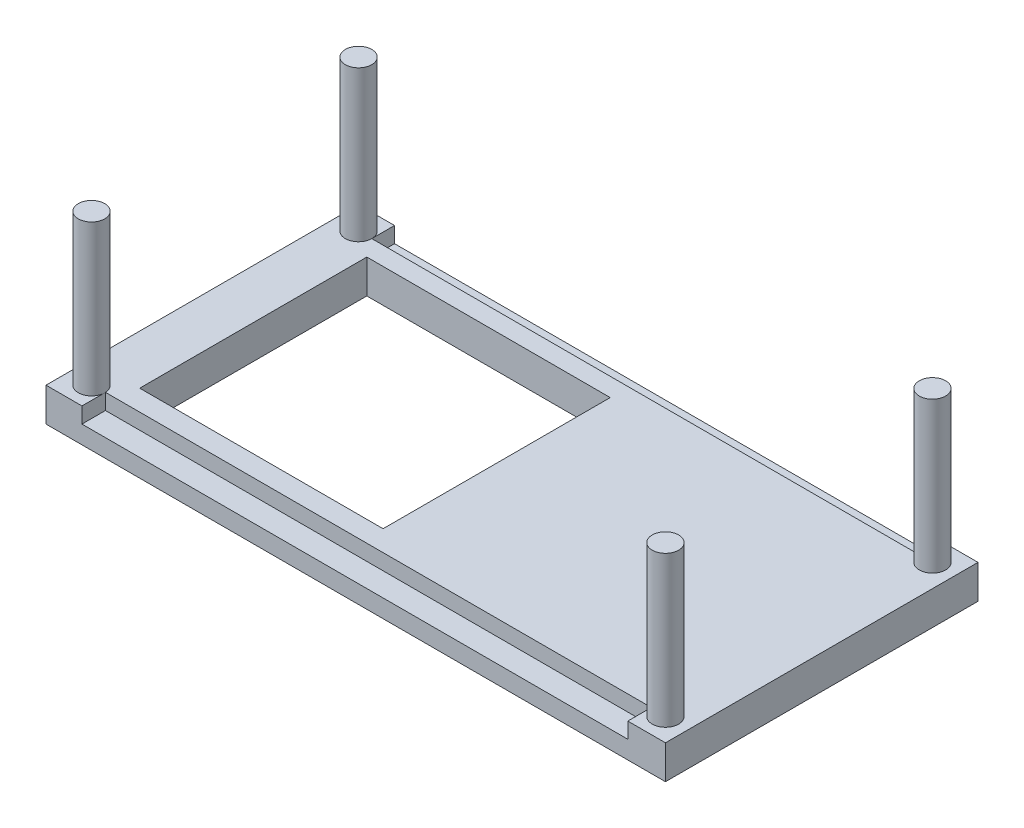
SolidWorks part; units mm, degrees
ref_plane "Front Plane" through (0, 0, 0) normal (0, 0, 1) x (1, 0, 0)
ref_plane "Top Plane" through (0, 0, 0) normal (0, 1, 0) x (1, 0, 0)
ref_plane "Right Plane" through (0, 0, 0) normal (1, 0, 0) x (0, 0, -1)
sketch "Sketch1" plane through (0, 0, 0) normal (0, 1, 0) x (1, 0, 0)
  line L1 (27.55, -13.9) -> (-27.55, -13.9)
  line L2 (27.55, -13.9) -> (27.55, 13.9)
  line L3 (27.55, 13.9) -> (-27.55, 13.9)
  line L4 (-27.55, -13.9) -> (-27.55, 13.9)
  line L5 (27.55, -13.9) -> (-27.55, 13.9) construction
  line L6 (27.55, 13.9) -> (-27.55, -13.9) construction
  point P0 (0, 0)
  dimension "D1" = 27.8
  dimension "D2" = 55.1
extrude "Boss-Extrude1" add sketch "Sketch1" along normal blind 3
sketch "Sketch2" plane through (0, 3, 0) normal (0, 1, 0) x (1, 0, 0)
  line L0 (26.7, -11.875) -> (27.55, -11.875)
  line L1 (25.525, -13.05) -> (25.525, -13.9)
  line L2 (-27.55, -13.9) -> (27.55, -13.9) construction
  line L3 (27.55, -13.9) -> (27.55, 13.9) construction
  line L4 (25.525, 13.05) -> (25.525, 13.9)
  line L5 (27.55, 13.9) -> (-27.55, 13.9) construction
  line L6 (26.7, 11.875) -> (27.55, 11.875)
  line L7 (-25.525, 13.05) -> (-25.525, 13.9)
  line L8 (-26.7, 11.875) -> (-27.55, 11.875)
  line L9 (-27.55, 13.9) -> (-27.55, -13.9) construction
  line L10 (-26.7, -11.875) -> (-27.55, -11.875)
  line L11 (-25.525, -13.05) -> (-25.525, -13.9)
  circle A0 centre (25.525, -11.875) radius 1.175
  circle A1 centre (25.525, 11.875) radius 1.175
  circle A2 centre (-25.525, 11.875) radius 1.175
  circle A3 centre (-25.525, -11.875) radius 1.175
  dimension "D1" = 2.35
  dimension "D2" = 0.85
  dimension "D4" = 2.35
  dimension "D7" = 2.35
  dimension "D10" = 2.35
  dimension "D3" = 0.85
  dimension "D5" = 0.85
  dimension "D6" = 0.85
  dimension "D8" = 0.85
  dimension "D9" = 0.85
  dimension "D11" = 0.85
  dimension "D12" = 0.85
extrude "Boss-Extrude2" add sketch "Sketch2" along normal blind 13.4 contours A2 | A3 | A1 | A0
sketch "Sketch3" plane through (0, 0, 0) normal (0, -1, 0) x (1, 0, 0)
  line L0 (-27.55, -13.9) -> (-27.55, 13.9) construction
  line L1 (-3.5, -8.25) -> (-21.15, -8.25)
  line L2 (-3.5, -8.25) -> (-3.5, 7.5)
  line L3 (-3.5, 7.5) -> (-21.15, 7.5)
  line L4 (-21.15, -8.25) -> (-21.15, 7.5)
  line L5 (-27.55, 13.9) -> (27.55, 13.9) construction
  line L6 (27.55, -13.9) -> (-27.55, -13.9) construction
  line L8 (-1.5, -10.2373) -> (-23.15, -10.2373)
  line L9 (-1.5, -10.2373) -> (-1.5, 9.9665)
  line L10 (-1.5, 9.9665) -> (-23.15, 9.9665)
  line L11 (-23.15, -10.2373) -> (-23.15, 9.9665)
  line L12 (-3.5, 7.5) -> (-21.15, 7.5)
  line L13 (-3.5, 7.5) -> (-3.5, -8.25)
  line L14 (-3.5, -8.25) -> (-21.15, -8.25)
  line L15 (-21.15, 7.5) -> (-21.15, -8.25)
  dimension "D1" = 15.75
  dimension "D2" = 17.65
  dimension "D3" = 6.4
  dimension "D4" = 6.4
  dimension "D5" = 5.65
  dimension "D6" = 2
  dimension "D7" = 20.2038
  dimension "D8" = 2
  dimension "D9" = 2.4665
extrude "Cut-Extrude1" cut sketch "Sketch3" against normal through all contours L4 L1 L2 L3 | L11 L8 L9 L10 L1 L4 L3 L2
sketch "Sketch6" plane through (0, 3, 0) normal (0, 1, 0) x (1, 0, 0)
  line L0 (-27.55, -13.9) -> (27.55, -13.9) construction
  line L9 (-24.3519, -11.8086) -> (24.2, -11.8086)
  line L10 (-24.3519, -11.8086) -> (-24.3519, -13.9)
  line L11 (-24.3519, -13.9) -> (24.2, -13.9)
  line L12 (24.2, -11.8086) -> (24.2, -13.9)
  line L13 (-24.35, 11.875) -> (24.35, 11.875)
  line L14 (-24.35, 11.875) -> (-24.35, 16.459)
  line L15 (24.35, 11.875) -> (24.35, 16.459)
  line L16 (-24.35, 16.459) -> (24.35, 16.459)
  circle A0 centre (-25.525, -11.875) radius 1.175 construction
  circle A1 centre (-25.525, -11.875) radius 1.175 construction
  circle A2 centre (-25.525, 11.875) radius 1.175 construction
  circle A3 centre (-25.525, 11.875) radius 1.175 construction
  circle A4 centre (25.525, 11.875) radius 1.175 construction
extrude "Cut-Extrude2" cut sketch "Sketch6" against normal blind 1.4
